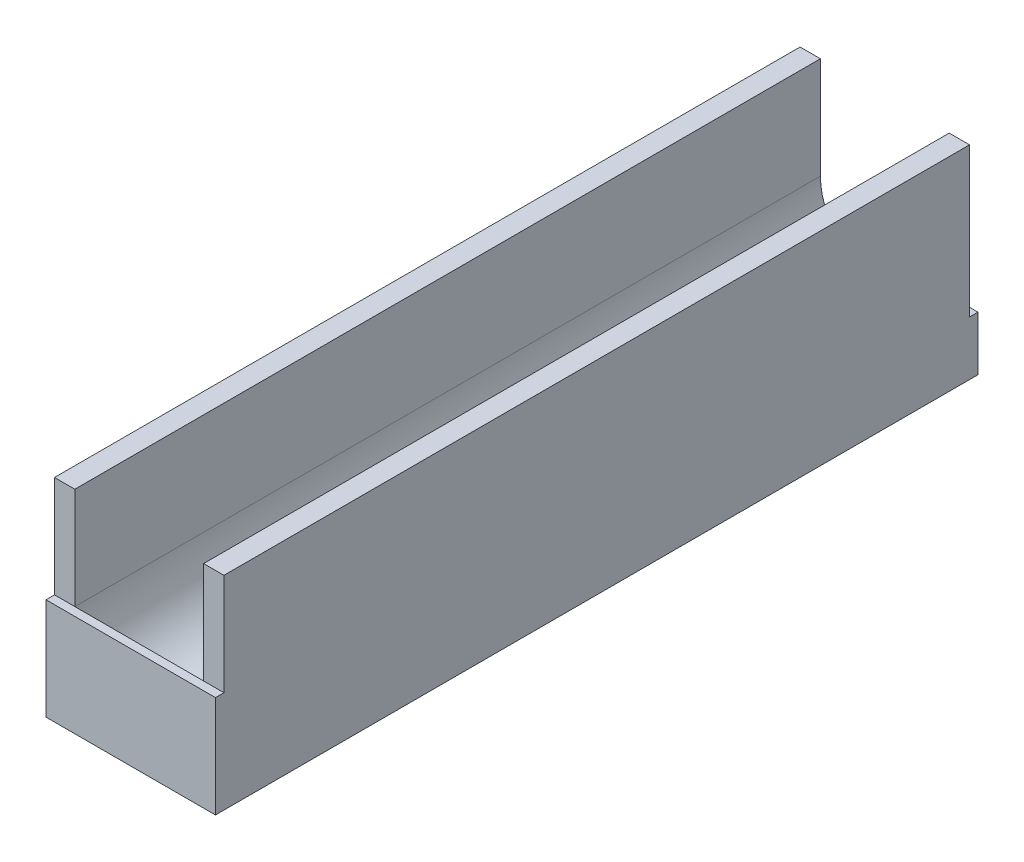
SolidWorks part; units mm, degrees
ref_plane "Front Plane" through (0, 0, 0) normal (0, 0, 1) x (1, 0, 0)
ref_plane "Top Plane" through (0, 0, 0) normal (0, 1, 0) x (1, 0, 0)
ref_plane "Right Plane" through (0, 0, 0) normal (1, 0, 0) x (0, 0, -1)
sketch "Sketch1" plane through (0, 0, 0) normal (0, 0, 1) x (1, 0, 0)
  line L1 (-15.875, 0) -> (15.875, 0)
  line L2 (-15.875, 0) -> (-15.875, 38.1)
  line L3 (-15.875, 38.1) -> (15.875, 38.1)
  line L4 (15.875, 0) -> (15.875, 38.1)
  dimension "D1" = 38.1
  dimension "D2" = 31.75
  dimension "D3" = 15.875
extrude "Boss-Extrude1" add sketch "Sketch1" along normal blind 139.7
sketch "Sketch2" plane through (0, 0, 139.7) normal (0, 0, 1) x (1, 0, 0)
  line L0 (-12.065, 19.05) -> (-12.065, 38.1)
  line L1 (15.875, 38.1) -> (-15.875, 38.1) construction
  line L2 (12.065, 19.05) -> (12.065, 38.1)
  line L3 (12.065, 38.1) -> (-12.065, 38.1)
  arc A2 (-12.065, 19.05) -> (12.065, 19.05) centre (0, 19.05) ccw
  dimension "D1" = 24.13
  dimension "D3" = 19.05
  dimension "D2" = 0
  dimension "D4" = 19.05
extrude "Cut-Extrude1" cut sketch "Sketch2" against normal through all
sketch "Sketch3" plane through (0, 0, 0) normal (0, -1, 0) x (1, 0, 0)
  line L0 (-15.875, 139.7) -> (15.875, 139.7) construction
  line L1 (-15.875, 0) -> (15.875, 0) construction
  circle A0 centre (-12.7, 130.81) radius 2
  circle A1 centre (12.7, 8.89) radius 2
  point P6 (0, 139.7)
  dimension "D1" = 4
  dimension "D2" = 4
  dimension "D6" = 8.89
  dimension "D3" = 12.7
  dimension "D4" = 12.7
  dimension "D5" = 8.89
extrude "heat set insert holes" cut sketch "Sketch3" against normal blind 7
sketch "Sketch4" plane through (0, 0, 139.7) normal (0, 0, 1) x (1, 0, 0)
  line L0 (-15.875, 38.1) -> (-15.875, 0) construction
  line L1 (15.875, 0) -> (-15.875, 0)
  line L2 (15.875, 0) -> (15.875, 19.05)
  line L3 (15.875, 19.05) -> (-15.875, 19.05)
  line L4 (-15.875, 0) -> (-15.875, 19.05)
  dimension "D1" = 19.05
extrude "Boss-Extrude2" add sketch "Sketch4" along normal blind 1.5875
sketch "Sketch5" plane through (0, 0, 0) normal (0, 0, -1) x (-1, 0, 0)
  line L0 (15.875, 38.1) -> (15.875, 0) construction
  line L1 (-15.875, 0) -> (15.875, 0)
  line L2 (-15.875, 0) -> (-15.875, 10.16)
  line L3 (-15.875, 10.16) -> (15.875, 10.16)
  line L4 (15.875, 0) -> (15.875, 10.16)
  dimension "D1" = 10.16
extrude "Boss-Extrude3" add sketch "Sketch5" along normal blind 1.5875
